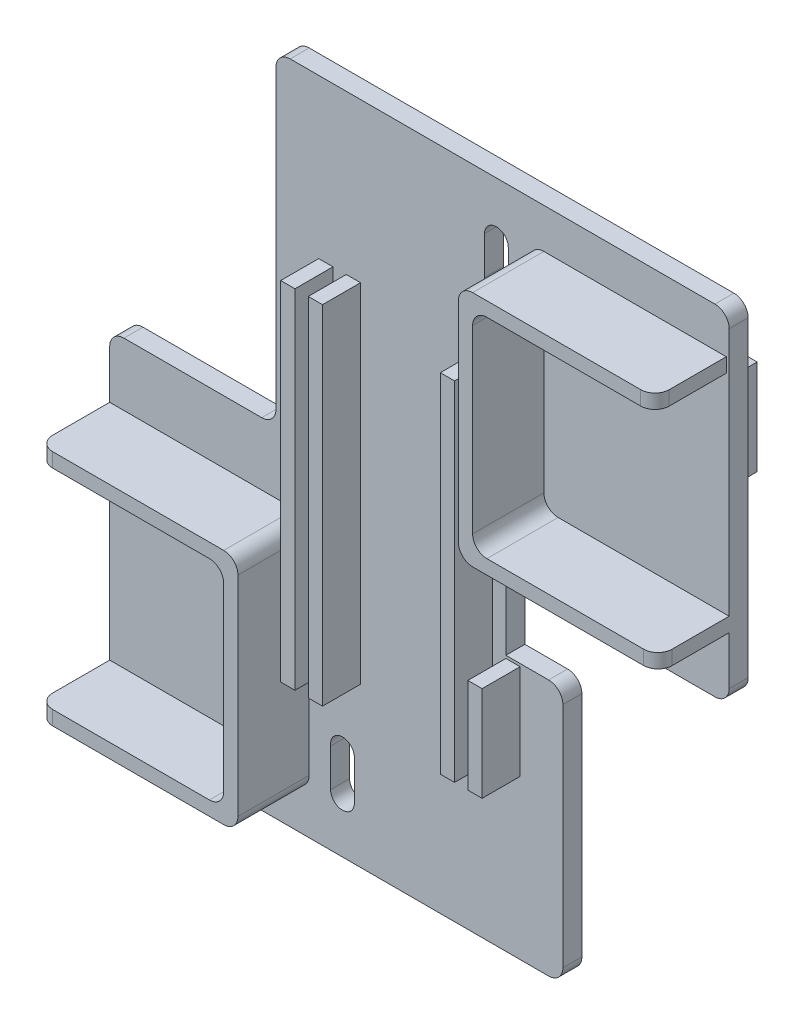
SolidWorks part; units mm, degrees
ref_plane "Front Plane" through (0, 0, 0) normal (0, 0, 1) x (1, 0, 0)
ref_plane "Top Plane" through (0, 0, 0) normal (0, 1, 0) x (1, 0, 0)
ref_plane "Right Plane" through (0, 0, 0) normal (1, 0, 0) x (0, 0, -1)
sketch "Sketch3" plane through (0, 0, 0) normal (0, 0, 1) x (1, 0, 0)
  line L0 (-6.95, 0) -> (6.95, 0) construction
  line L2 (-7.7, 18.3) -> (-6.2, 18.3)
  line L3 (-7.7, 18.3) -> (-7.7, -18.3)
  line L4 (-7.7, -18.3) -> (-6.2, -18.3)
  line L5 (-6.2, 18.3) -> (-6.2, -18.3)
  line L6 (-7.7, 18.3) -> (-6.2, -18.3) construction
  line L7 (-7.7, -18.3) -> (-6.2, 18.3) construction
  line L8 (-10.6, 18.3) -> (-9.1, 18.3)
  line L9 (-10.6, 18.3) -> (-10.6, -18.3)
  line L10 (-10.6, -18.3) -> (-9.1, -18.3)
  line L11 (-9.1, 18.3) -> (-9.1, -18.3)
  line L12 (-10.6, 18.3) -> (-9.1, -18.3) construction
  line L13 (-10.6, -18.3) -> (-9.1, 18.3) construction
  line L14 (6.2, 18.3) -> (7.7, 18.3)
  line L15 (6.2, 18.3) -> (6.2, -18.3)
  line L16 (6.2, -18.3) -> (7.7, -18.3)
  line L17 (7.7, 18.3) -> (7.7, -18.3)
  line L18 (6.2, 18.3) -> (7.7, -18.3) construction
  line L19 (6.2, -18.3) -> (7.7, 18.3) construction
  line L20 (10.6, 18.3) -> (9.1, 18.3)
  line L21 (10.6, 18.3) -> (10.6, -18.3)
  line L22 (10.6, -18.3) -> (9.1, -18.3)
  line L23 (9.1, 18.3) -> (9.1, -18.3)
  line L24 (10.6, 18.3) -> (9.1, -18.3) construction
  line L25 (10.6, -18.3) -> (9.1, 18.3) construction
  point P3 (-9.85, 0)
  point P16 (9.85, 0)
  dimension "D1" = 6.95
  dimension "D2" = 6.95
  dimension "D3" = 36.6
  dimension "D4" = 36.6
  dimension "D5" = 36.6
  dimension "D6" = 36.6
  dimension "D7" = 0
  dimension "D8" = 0
  dimension "D9" = 1.5
  dimension "D10" = 1.5
  dimension "D11" = 1.4
  dimension "D12" = 1.5
  dimension "D13" = 1.4
  dimension "D14" = 1.5
extrude "Boss-Extrude1" add sketch "Sketch3" along normal blind 4
sketch "Sketch4" plane through (0, 0, 0) normal (0, 0, 1) x (1, 0, 0)
  line L1 (-32.6, 35) -> (32.6, 35)
  line L2 (-32.6, 35) -> (-32.6, -35)
  line L3 (-32.6, -35) -> (32.6, -35)
  line L4 (32.6, 35) -> (32.6, -35)
  line L5 (-32.6, 35) -> (32.6, -35) construction
  line L6 (-32.6, -35) -> (32.6, 35) construction
  point P0 (0, 0)
  dimension "D1" = 70
  dimension "D2" = 65.2
extrude "Boss-Extrude2" add sketch "Sketch4" against normal blind 2
sketch "Sketch5" plane through (0, 0, 0) normal (0, 0, 1) x (1, 0, 0)
  line L0 (11.6, 30.8) -> (11.6, 5.8)
  line L1 (11.6, 5.8) -> (32.6, 5.8)
  line L2 (32.6, 5.8) -> (32.6, 7.3)
  line L3 (32.6, 7.3) -> (13.1, 7.3)
  line L4 (13.1, 7.3) -> (13.1, 29.3)
  line L5 (13.1, 29.3) -> (32.2947, 29.3)
  line L6 (32.2947, 29.3) -> (32.2947, 30.8)
  line L7 (32.2947, 30.8) -> (11.6, 30.8)
  line L8 (-32.6, -5.8) -> (-11.6, -5.8)
  line L9 (-11.6, -5.8) -> (-11.6, -30.8)
  line L10 (-11.6, -30.8) -> (-32.6, -30.8)
  line L11 (-32.6, -30.8) -> (-32.6, -29.3)
  line L12 (-32.6, -29.3) -> (-13.1, -29.3)
  line L13 (-13.1, -29.3) -> (-13.1, -7.3)
  line L14 (-13.1, -7.3) -> (-32.6, -7.3)
  line L15 (-32.6, -5.8) -> (-32.6, -7.3)
  line L16 (10.6, -18.3) -> (10.6, 18.3) construction
  line L17 (-7.7, -18.3) -> (-6.2, -18.3) construction
  line L18 (10.6, 18.3) -> (9.1, 18.3) construction
  line L19 (-10.6, 18.3) -> (-10.6, -18.3) construction
  dimension "D1" = 21
  dimension "D2" = 19.5
  dimension "D3" = 22
  dimension "D4" = 25
  dimension "D5" = 1.5
  dimension "D6" = 1
  dimension "D7" = 21
  dimension "D8" = 19.5
  dimension "D9" = 22
  dimension "D10" = 25
  dimension "D11" = 1.5
  dimension "D12" = 11
  dimension "D13" = 11
  dimension "D14" = 1
  dimension "D15" = 21
extrude "Boss-Extrude3" add sketch "Sketch5" along normal blind 7.5
sketch "Sketch6" plane through (0, 0, 0) normal (0, 0, 1) x (1, 0, 0)
  line L0 (-32.6, 35) -> (-32.6, -5.8) construction
  line L1 (-32.6, 30) -> (-15.1, 30)
  line L2 (-32.6, 30) -> (-32.6, 0.8)
  line L3 (-32.6, 0.8) -> (-15.1, 0.8)
  line L4 (-15.1, 30) -> (-15.1, 0.8)
  line L5 (32.6, -35) -> (32.6, 5.8) construction
  line L6 (32.6, -0.8) -> (15.1, -0.8)
  line L7 (32.6, -0.8) -> (32.6, -30)
  line L8 (32.6, -30) -> (15.1, -30)
  line L9 (15.1, -0.8) -> (15.1, -30)
  line L10 (-32.6, -35) -> (32.6, -35) construction
other "AlignGroup1" parameters "D1"=19.5486, "D2"=19.4425, "D3"=5, "D4"=4.2814, "D5"=26.6576, "D6"=24.8537
extrude "Cut-Extrude1" cut sketch "Sketch6" against normal blind 4
sketch "Sketch10" plane through (0, 0, -2) normal (0, 0, -1) x (-1, 0, 0)
  line L0 (-13.1, 7.3) -> (-13.1, 29.3) construction
  line L1 (-13.1, 29.3) -> (-32.2947, 29.3) construction
  line L3 (13.1, -29.3) -> (32.6, -29.3) construction
  line L4 (13.1, -7.3) -> (13.1, -29.3) construction
  circle A0 centre (-15.1, 27.3) radius 1.5
  circle A1 centre (15.1, -27.3) radius 1.5
  dimension "D1" = 3
  dimension "D2" = 3
  dimension "D3" = 2
  dimension "D4" = 2
  dimension "D5" = 2
  dimension "D6" = 2
extrude "Cut-Extrude5" cut sketch "Sketch10" against normal blind 20
sketch "Sketch11" plane through (0, 0, 0) normal (0, 0, 1) x (1, 0, 0)
  line L0 (-15.1, 0.8) -> (-15.1, 30) construction
  line L1 (-15.1, 25.8376) -> (-38.7298, 25.8376)
  line L2 (-15.1, 25.8376) -> (-15.1, 39.6317)
  line L3 (-15.1, 39.6317) -> (-38.7298, 39.6317)
  line L4 (-38.7298, 25.8376) -> (-38.7298, 39.6317)
  line L5 (15.1, -0.8) -> (15.1, -30) construction
  line L6 (15.1, -25.5192) -> (34.5916, -25.5192)
  line L7 (15.1, -25.5192) -> (15.1, -38.2523)
  line L8 (15.1, -38.2523) -> (34.5916, -38.2523)
  line L9 (34.5916, -25.5192) -> (34.5916, -38.2523)
  line L10 (-32.6, -30.8) -> (-11.6, -30.8) construction
  line L11 (-32.6, -35) -> (32.6, -35) construction
  line L12 (32.6, 35) -> (-32.6, 35) construction
  line L13 (32.2947, 30.8) -> (11.6, 30.8) construction
  dimension "D1" = 4.2
  dimension "D2" = 4.2
extrude "Cut-Extrude6" cut sketch "Sketch11" against normal blind 20
sketch "Sketch13" plane through (10.6, 0, 0) normal (1, 0, 0) x (0, 0, -1)
  line L0 (-4, -18.3) -> (-4, 18.3) construction
  line L1 (-4, -8.3) -> (0, -8.3)
  line L2 (-4, -8.3) -> (-4, 8.3)
  line L3 (-4, 8.3) -> (0, 8.3)
  line L4 (0, -8.3) -> (0, 8.3)
  line L5 (0, -0.8) -> (0, 5.8) construction
  line L6 (-4, -18.3) -> (0, -18.3) construction
  line L7 (-4, 18.3) -> (0, 18.3) construction
  dimension "D1" = 10
  dimension "D2" = 10
extrude "Cut-Extrude7" cut sketch "Sketch13" against normal blind 2
sketch "Sketch15" plane through (0, 0, 0) normal (0, 0, 1) x (1, 0, 0)
  line L0 (9.1, 10.1814) -> (9.1, -10.3863) construction
  line L1 (9.1, 18.3) -> (9.1, 8.3) construction
  line L2 (9.1, -8.3) -> (9.1, -18.3) construction
  line L4 (9.1, 5.8) -> (15.1, 5.8)
  line L5 (9.1, 5.8) -> (9.1, -5.8)
  line L6 (9.1, -5.8) -> (15.1, -5.8)
  line L7 (15.1, 5.8) -> (15.1, -5.8)
  line L8 (10.6, -8.3) -> (9.1, -8.3) construction
  line L9 (11.6, 5.8) -> (32.6, 5.8) construction
  line L10 (15.1, -0.8) -> (15.1, -35) construction
  dimension "D1" = 0
  dimension "D2" = 2.5
  dimension "D3" = 0
extrude "Cut-Extrude8" cut sketch "Sketch15" against normal blind 2
sketch "Sketch16" plane through (0, 0, 0) normal (0, 0, 1) x (1, 0, 0)
  line L2 (-13.1, -29.3) -> (-32.6, -29.3) construction
  line L3 (-6.85, -25.3) -> (-6.85, -29.4806)
  line L5 (-9.35, -29.4806) -> (-9.3369, -25.4806)
  line L7 (-11.6, -30.8) -> (-11.6, -5.8) construction
  line L8 (11.6, 29.3) -> (8.1, 29.3) construction
  line L9 (11.6, 30.8) -> (11.6, 5.8) construction
  line L10 (6.85, 29.3) -> (6.85, 25.3)
  line L11 (13.1, 29.3) -> (32.2947, 29.3) construction
  line L12 (9.35, 25.3) -> (9.35, 29.3)
  arc A0 (-6.85, -25.3) -> (-9.3369, -25.4806) centre (-8.1, -25.3) ccw
  arc A1 (-9.35, -29.4806) -> (-6.85, -29.4806) centre (-8.1, -29.4806) ccw
  arc A2 (9.35, 29.3) -> (6.85, 29.3) centre (8.1, 29.3) ccw
  arc A3 (6.85, 25.3) -> (9.35, 25.3) centre (8.1, 25.3) ccw
  dimension "D1" = 2.5
  dimension "D2" = 2.5
  dimension "D7" = 2.5
  dimension "D8" = 2.5
  dimension "D3" = 4
  dimension "D4" = 4
  dimension "D5" = 3.5
  dimension "D6" = 3.5
  dimension "D9" = 4
  dimension "D10" = 0
extrude "Cut-Extrude9" cut sketch "Sketch16" against normal blind 2
fillet "Fillet1" radius 1.5 22 edges at (32.6, 35, -1) (15.1, -35, -1) (13.1, 7.3, 3.75) (13.1, 29.3, 3.75) (32.2947, 30.05, 7.5) (32.6, 6.55, 7.5) (32.6, -0.8, -1) (15.1, -0.8, -1) (15.1, 5.8, -1) (15.1, -5.8, -1) (-32.6, -6.55, 7.5) (-32.6, -30.05, 7.5) (-13.1, -29.3, 3.75) (-13.1, -7.3, 3.75) (-32.6, -35, -1) (-32.6, 0.8, -1) (-15.1, 0.8, -1) (-15.1, 35, -1) (11.6, 5.8, 3.75) (11.6, 30.8, 3.75) (-11.6, -30.8, 3.75) (-11.6, -5.8, 3.75)
sketch "Sketch18" plane through (0, 0, 0) normal (0, 0, 1) x (1, 0, 0)
  line L0 (11.6, 29.3) -> (11.6, 7.3) construction
  line L1 (9.1, 8.3) -> (11.6, 8.3)
  line L2 (9.1, 8.3) -> (9.1, -8.0112)
  line L4 (11.6, 8.3) -> (11.6, -5.8)
  line L5 (11.6, -5.8) -> (16.4955, -5.8)
  line L7 (16.4955, -5.8) -> (16.4955, -8.0112)
  line L8 (9.1, -8.0112) -> (16.4955, -8.0112)
  dimension "D1" = 0
extrude "Cut-Extrude11" cut sketch "Sketch18" against normal blind 2
fillet "Fillet2" radius 1.5 2 edges at (11.6, 5.8, -1) (15.1, -8.0112, -1)
sketch "Sketch19" plane through (0, 0, -2) normal (0, 0, -1) x (-1, 0, 0)
  line L0 (-31.1, 35) -> (13.6, 35) construction
  line L1 (-32.6, 0.7) -> (-32.6, 33.5) construction
  line L2 (31.1, -35) -> (-13.6, -35) construction
  line L3 (32.6, -0.7) -> (32.6, -33.5) construction
  line L5 (-18.6, 25) -> (-28.6, 25)
  line L6 (-18.6, 25) -> (-18.6, 15)
  line L7 (-18.6, 15) -> (-28.6, 15)
  line L8 (-28.6, 25) -> (-28.6, 15)
  line L9 (-18.6, 25) -> (-28.6, 15) construction
  line L10 (-18.6, 15) -> (-28.6, 25) construction
  line L11 (28.6, -15) -> (18.6, -15)
  line L12 (28.6, -15) -> (28.6, -25)
  line L13 (28.6, -25) -> (18.6, -25)
  line L14 (18.6, -15) -> (18.6, -25)
  line L15 (28.6, -15) -> (18.6, -25) construction
  line L16 (28.6, -25) -> (18.6, -15) construction
  point P8 (-23.6, 20)
  point P13 (23.6, -20)
  dimension "D1" = 4
  dimension "D2" = 4
  dimension "D3" = 10
  dimension "D4" = 10
  dimension "D5" = 10
  dimension "D6" = 10
  dimension "D7" = 15
  dimension "D8" = 15
extrude "Boss-Extrude5" add sketch "Sketch19" along normal blind 4.95
